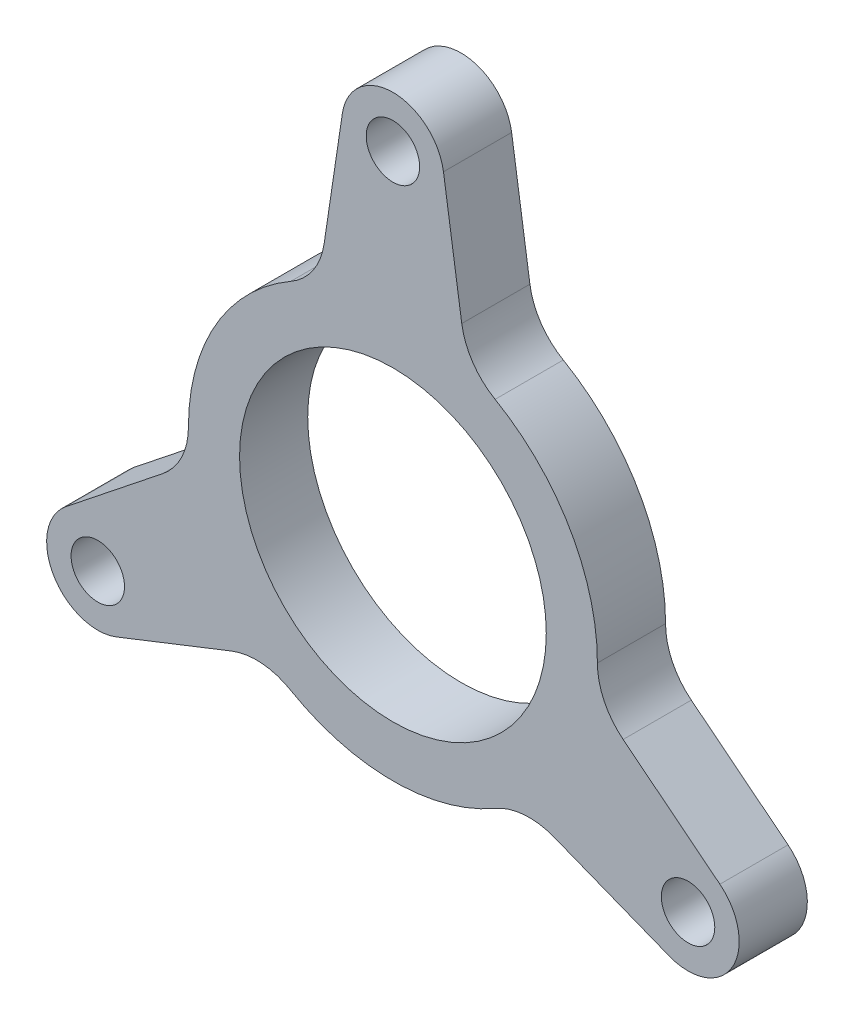
SolidWorks part; units mm, degrees
material "6061-T6 (SS)"
ref_plane "Front Plane" through (0, 0, 0) normal (0, 0, 1) x (1, 0, 0)
ref_plane "Top Plane" through (0, 0, 0) normal (0, 1, 0) x (1, 0, 0)
ref_plane "Right Plane" through (0, 0, 0) normal (1, 0, 0) x (0, 0, -1)
sketch "Sketch2" plane through (0, 0, 0) normal (0, 0, 1) x (1, 0, 0)
  line L3 (-4.7102, 32.4539) -> (-6.9072, 17.7537)
  line L4 (4.7102, 32.4539) -> (6.9072, 17.7537)
  line L5 (30.461, -12.1478) -> (18.8287, -2.8951)
  line L6 (25.7508, -20.3061) -> (11.9216, -14.8586)
  line L7 (-25.7508, -20.3061) -> (-11.9216, -14.8586)
  line L8 (-30.461, -12.1478) -> (-18.8287, -2.8951)
  line L9 (0, 31.75) -> (0, 0) construction
  circle A0 centre (0, 0) radius 14.2875
  circle A1 centre (0, 31.75) radius 2.4892
  circle A2 centre (27.4963, -15.875) radius 2.4892
  circle A3 centre (-27.4963, -15.875) radius 2.4892
  circle A4 centre (27.4963, -15.875) radius 4.7625
  circle A5 centre (0, 31.75) radius 4.7625
  circle A6 centre (-27.4963, -15.875) radius 4.7625
  circle A7 centre (0, 0) radius 19.05
  point P11 (0, 0)
  point P28 (0, 0)
  point P33 (0, 0)
  dimension "D1" = 28.575
  dimension "D2" = 4.9784
  dimension "D6" = 9.525
  dimension "D5" = 38.1
  dimension "D3" = 31.75
  dimension "D7" = 8.5
  dimension "D8" = 8.5
  dimension "D4" = 3
  dimension "D9" = 3
extrude "Boss-Extrude1" add sketch "Sketch2" along normal blind 6.35
fillet "Fillet2" radius 6.35 6 edges at (18.8287, -2.8951, 3.175) (11.9216, -14.8586, 3.175) (-11.9216, -14.8586, 3.175) (-18.8287, -2.8951, 3.175) (-6.9072, 17.7537, 3.175) (6.9072, 17.7537, 3.175)
equation "\"D8@Sketch2\"=\"D7@Sketch2\""
